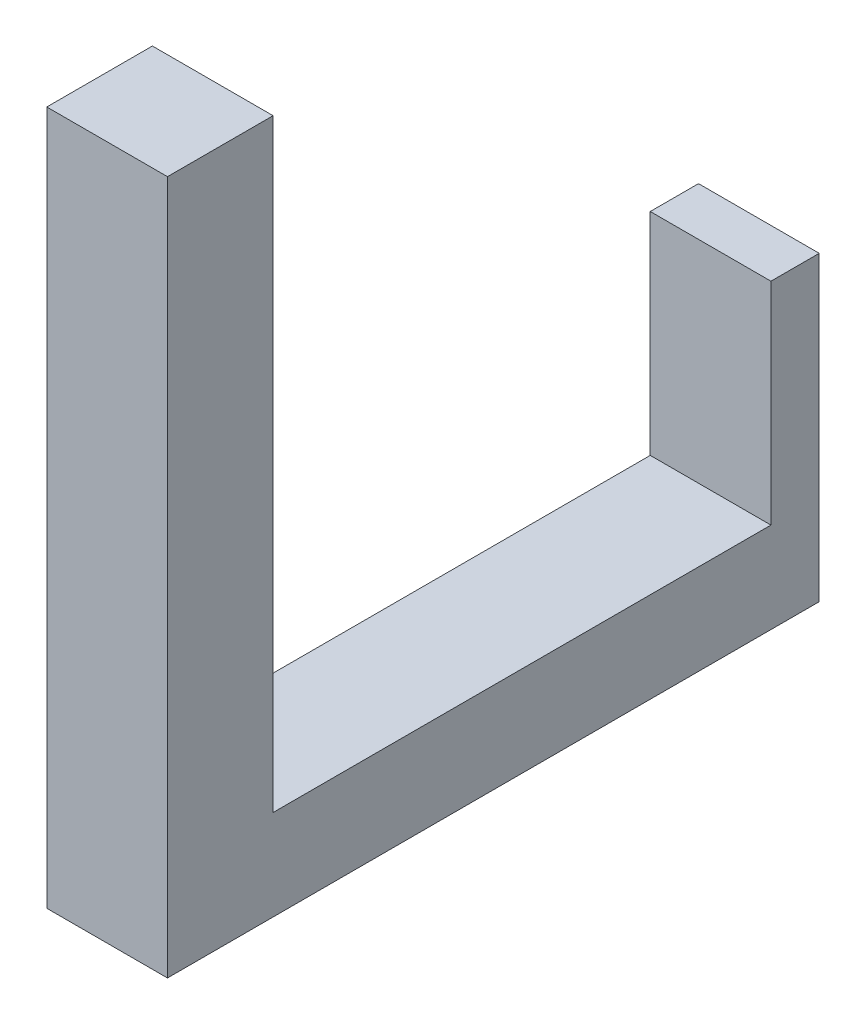
SolidWorks part; units mm, degrees
ref_plane "前视基准面" through (0, 0, 0) normal (0, 0, 1) x (1, 0, 0)
ref_plane "上视基准面" through (0, 0, 0) normal (0, 1, 0) x (1, 0, 0)
ref_plane "右视基准面" through (0, 0, 0) normal (1, 0, 0) x (0, 0, -1)
other "Configuration Table"
sketch "草图1" plane through (0, 0, 0) normal (0, 1, 0) x (1, 0, 0)
  line L1 (-20, 8) -> (20, 8)
  line L2 (-20, 8) -> (-20, -8)
  line L3 (-20, -8) -> (20, -8)
  line L4 (20, 8) -> (20, -8)
  line L5 (-20, 8) -> (20, -8) construction
  line L6 (-20, -8) -> (20, 8) construction
  point P0 (0, 0)
  dimension "D1" = 40
  dimension "D2" = 16
extrude "凸台-拉伸1" add sketch "草图1" along normal blind 100
sketch "草图2" plane through (0, 0, 8) normal (0, 0, 1) x (1, 0, 0)
  line L0 (-20, 100) -> (-20, 0) construction
  line L1 (-20, 30) -> (20, 30)
  line L2 (-20, 30) -> (-20, 0)
  line L3 (-20, 0) -> (20, 0)
  line L4 (20, 30) -> (20, 0)
  dimension "D1" = 40
  dimension "D2" = 30
extrude "凸台-拉伸2" add sketch "草图2" along normal blind 200 contours L2 L1 L4 L3
sketch "草图3" plane through (0, 30, 0) normal (0, 1, 0) x (1, 0, 0)
  line L0 (-20, -208) -> (-20, -8) construction
  line L1 (-20, -173) -> (20, -173)
  line L2 (-20, -173) -> (-20, -208)
  line L3 (-20, -208) -> (20, -208)
  line L4 (20, -173) -> (20, -208)
  line L5 (20, -208) -> (20, -8) construction
  dimension "D1" = 40
  dimension "D2" = 35
extrude "凸台-拉伸3" add sketch "草图3" along normal blind 200
